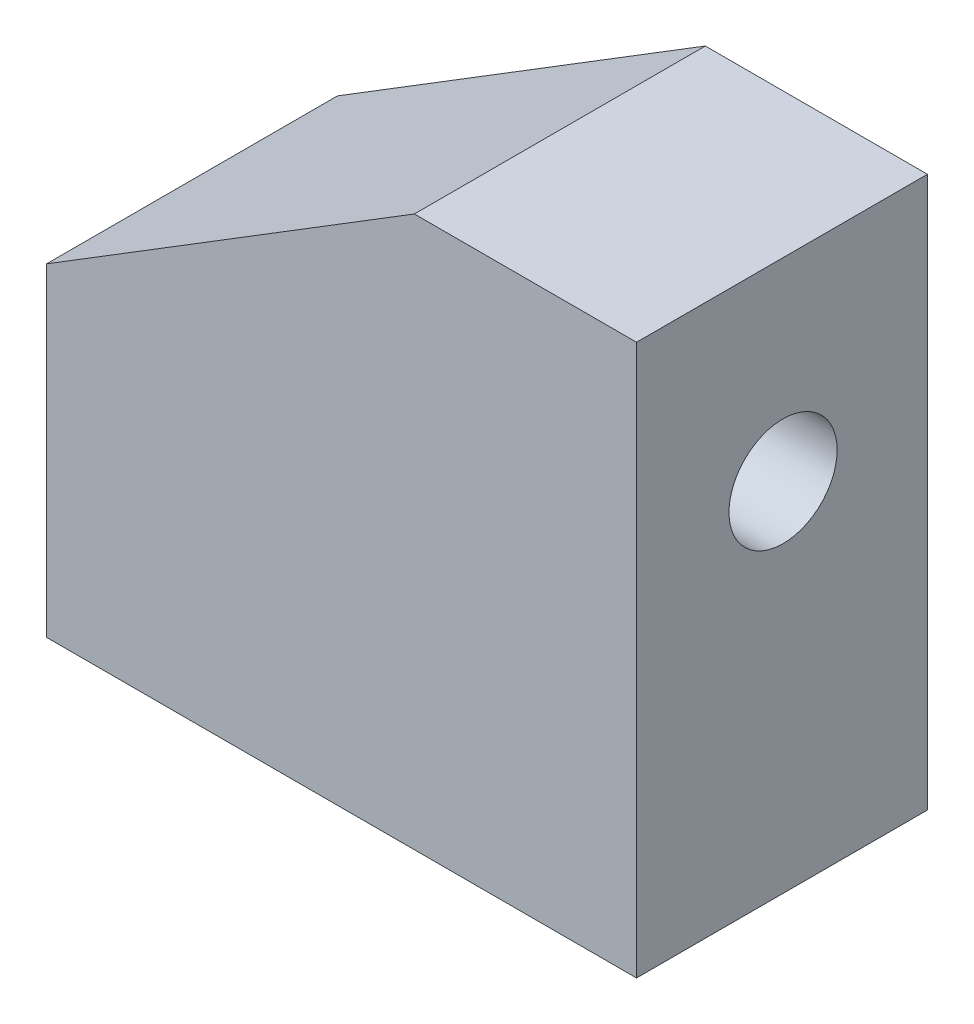
SolidWorks part; units mm, degrees
ref_plane "Front Plane" through (0, 0, 0) normal (0, 0, 1) x (1, 0, 0)
ref_plane "Top Plane" through (0, 0, 0) normal (0, 1, 0) x (1, 0, 0)
ref_plane "Right Plane" through (0, 0, 0) normal (1, 0, 0) x (0, 0, -1)
sketch "Sketch2" plane through (0, 0, 0) normal (0, 0, 1) x (1, 0, 0)
  line L0 (0, 0) -> (87.1992, 0)
  line L1 (87.1992, 0) -> (87.1992, 81.3756)
  line L2 (87.1992, 81.3756) -> (54.3636, 81.3756)
  line L3 (54.3636, 81.3756) -> (0, 47.8103)
  line L4 (0, 47.8103) -> (0, 0)
extrude "Boss-Extrude1" add sketch "Sketch2" along normal blind 43
sketch "Sketch3" plane through (87.1992, 0, 0) normal (1, 0, 0) x (0, 0, -1)
  circle A0 centre (-21.3426, 52.7563) radius 7.9923
extrude "Cut-Extrude1" cut sketch "Sketch3" against normal blind 20
